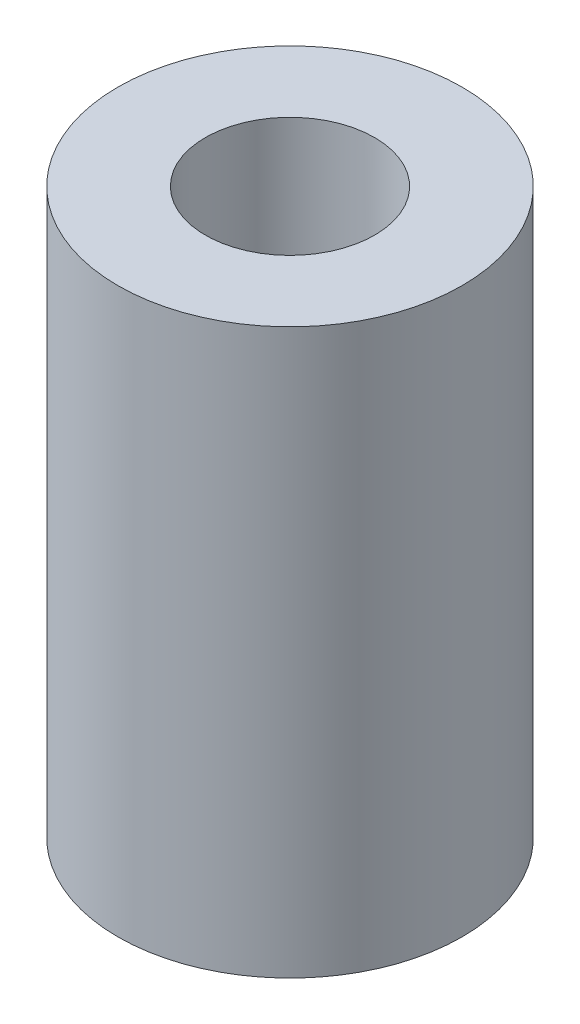
SolidWorks part; units mm, degrees
ref_plane "Alzado" through (0, 0, 0) normal (1, 0, 0) x (0, 1, 0)
ref_plane "Planta" through (0, 0, 0) normal (0, 0, 1) x (0, 1, 0)
ref_plane "Vista lateral" through (0, 0, 0) normal (0, 1, 0) x (-1, 0, 0)
sketch "Croquis1" plane through (0, 0, 0) normal (0, 1, 0) x (-1, 0, 0)
  circle A0 centre (0, 0) radius 6.1
  dimension "D1" = 12.2
extrude "Saliente-Extruir1" add sketch "Croquis1" along normal blind 20
sketch "Croquis2" plane through (0, 20, 0) normal (0, 1, 0) x (-1, 0, 0)
  line L0 (2.5981, 1.5) -> (-2.5981, 1.5)
  line L1 (0, 0) -> (0, 1.5) construction
  arc A0 (-2.5981, 1.5) -> (2.5981, 1.5) centre (0, 0) ccw
  dimension "D1" = 3
  dimension "D2" = 1.5
extrude "Saliente-Extruir2" [suppressed] add sketch "Croquis2" along normal blind 17
sketch "Croquis3" plane through (0, 0, 0) normal (0, -1, 0) x (1, 0, 0)
  circle A0 centre (0, 0) radius 3
  dimension "D1" = 6
extrude "Cortar-Extruir1" cut sketch "Croquis3" against normal through all
sketch "Croquis4" plane through (0, 0, 0) normal (0, 0, 1) x (0, 1, 0)
  line L0 (5, 6.1) -> (5, 0) construction
  line L2 (5, 0) -> (0, 0) construction
  line L3 (10, 6.1) -> (10, -6.1) construction
  line L4 (20, 6.1) -> (0, 6.1) construction
  line L5 (0, -6.1) -> (20, -6.1) construction
  line L6 (5, 0) -> (10, 0) construction
  circle A0 centre (5, 0) radius 1.5
  circle A1 centre (15, 0) radius 1.5
  point P1 (5, 0)
  point P2 (15, 0)
  dimension "D1" = 3
hole_wizard "Taladro de margen para M21" positions "Croquis4" profile "Croquis5" hole size "M2" standard "Ansi Metric"
sketch "Croquis5" plane through (0, 15, 0) normal (1, 0, 0) x (0, -1, 0)
  line L0 (0, 0) -> (0, 6.1)
  line L1 (0, 6.1) -> (1.3, 6.1)
  line L2 (1.3, 6.1) -> (1.3, 0)
  line L5 (1.3, 0) -> (0, 0)
  line L11 (0, -6.35) -> (0, 107.95) construction
  dimension "Diámetro de taladro hasta el siguiente" = 2.6
  dimension "Profundidad de taladro hasta el siguiente" = 6.1
cosmetic thread "Rosca cosmética1" parameters "D2"=2.87
cosmetic thread "Rosca cosmética2" parameters "D2"=2.87
sketch "Croquis6" plane through (0, 0, 0) normal (1, 0, 0) x (0, 1, 0)
  point P0 (5, 0)
  point P1 (15, 0)
hole_wizard "Taladro de margen para M32" [suppressed] positions "Croquis6" profile "Croquis7" hole size "M3" standard "Ansi Metric"
sketch "Croquis7" plane through (0, 5, 0) normal (0, 1, 0) x (0, 0, -1)
  line L0 (0, 0) -> (0, 6.1)
  line L1 (0, 6.1) -> (1.8, 6.1)
  line L2 (1.8, 6.1) -> (1.8, 0)
  line L5 (1.8, 0) -> (0, 0)
  line L11 (0, -6.35) -> (0, 107.95) construction
  dimension "Diámetro de taladro hasta el siguiente" = 3.6
  dimension "Profundidad de taladro hasta el siguiente" = 6.1
equation "\"D2@Croquis2\"=\"D1@Croquis2\"/2"
